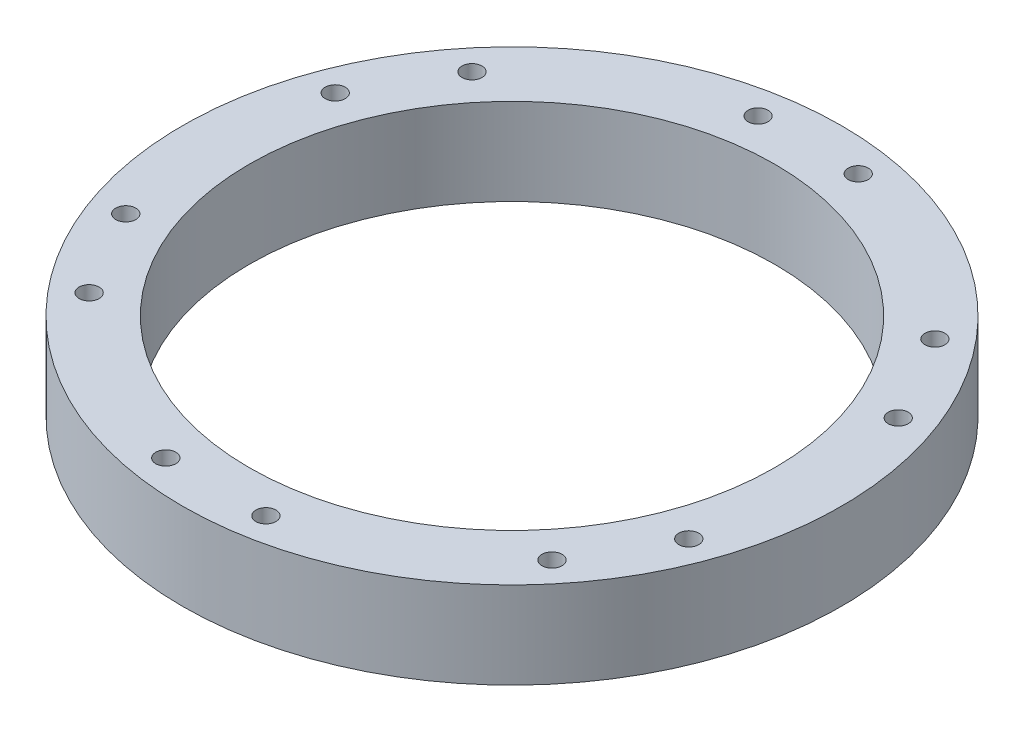
SolidWorks part; units mm, degrees
ref_plane "Front" through (0, 0, 0) normal (0, 0, 1) x (1, 0, 0)
ref_plane "Top" through (0, 0, 0) normal (0, 1, 0) x (1, 0, 0)
ref_plane "Right" through (0, 0, 0) normal (1, 0, 0) x (0, 0, -1)
sketch "Sketch1" plane through (0, 0, 0) normal (0, 1, 0) x (1, 0, 0)
  circle A0 centre (0, 0) radius 39.375
  circle A1 centre (0, 0) radius 49.375
  dimension "D1" = 78.75
  dimension "D2" = 10
extrude "Boss-Extrude1" add sketch "Sketch1" along normal blind 13
sketch "Sketch2" plane through (0, 13, 0) normal (0, 1, 0) x (1, 0, 0)
  line L0 (0, 0) -> (0, -49.375) construction
  line L1 (0, 0) -> (-8.2292, -48.6844) construction
  circle A0 centre (-7.5, -44.3706) radius 1.5
  circle A1 centre (7.5, -44.3706) radius 1.5
  circle A4 centre (0, 0) radius 49.375 construction
  circle A5 centre (0, 0) radius 45 construction
  dimension "D2" = 3
  dimension "D3" = 90
  dimension "D1" = 15
extrude "Cut-Extrude1" cut sketch "Sketch2" against normal up to next
pattern_circular "CirPattern1" count 6 over 360 about axis through (0, 0, 0) along (0, 1, 0) of "Cut-Extrude1"
